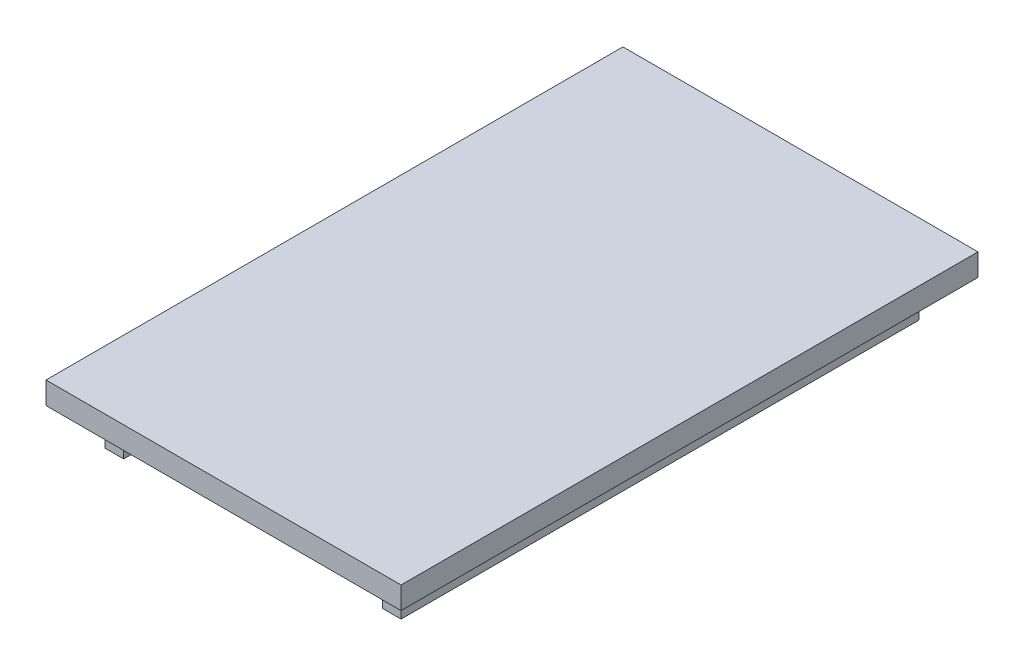
SolidWorks part; units mm, degrees
ref_plane "Alzado" through (0, 0, 0) normal (0, 0, 1) x (1, 0, 0)
ref_plane "Planta" through (0, 0, 0) normal (0, 1, 0) x (1, 0, 0)
ref_plane "Vista lateral" through (0, 0, 0) normal (1, 0, 0) x (0, 0, -1)
sketch "Croquis1" plane through (0, 0, 0) normal (0, 1, 0) x (1, 0, 0)
  line L1 (0, 0) -> (-40, 0)
  line L2 (0, 0) -> (0, -70)
  line L3 (0, -70) -> (-40, -70)
  line L4 (-40, 0) -> (-40, -70)
  dimension "D1" = 40
  dimension "D2" = 70
extrude "Saliente-Extruir1" add sketch "Croquis1" along normal blind 5
sketch "Croquis3" plane through (0, 5, 0) normal (0, 1, 0) x (1, 0, 0)
  line L5 (-44, -74) -> (4, -74)
  line L6 (-44, -74) -> (-44, 4)
  line L7 (-44, 4) -> (4, 4)
  line L8 (4, -74) -> (4, 4)
extrude "Saliente-Extruir3" add sketch "Croquis3" along normal blind 3
sketch "Croquis5" plane through (0, 0, 0) normal (0, -1, 0) x (1, 0, 0)
  line L0 (-40, 70) -> (-37.5, 70)
  line L1 (-40, 70) -> (0, 70) construction
  line L2 (0, 70) -> (-2.5, 70)
  line L3 (0, 0) -> (-40, 0) construction
  line L4 (-37.5, 70) -> (-2.5, 70)
  line L5 (-37.5, 70) -> (-37.5, 0)
  line L6 (-37.5, 0) -> (-2.5, 0)
  line L7 (-2.5, 70) -> (-2.5, 0)
  dimension "D1" = 2.5
  dimension "D2" = 2.5
extrude "Cortar-Extruir1" cut sketch "Croquis5" against normal blind 5 contours L5 L4 L7 L6
